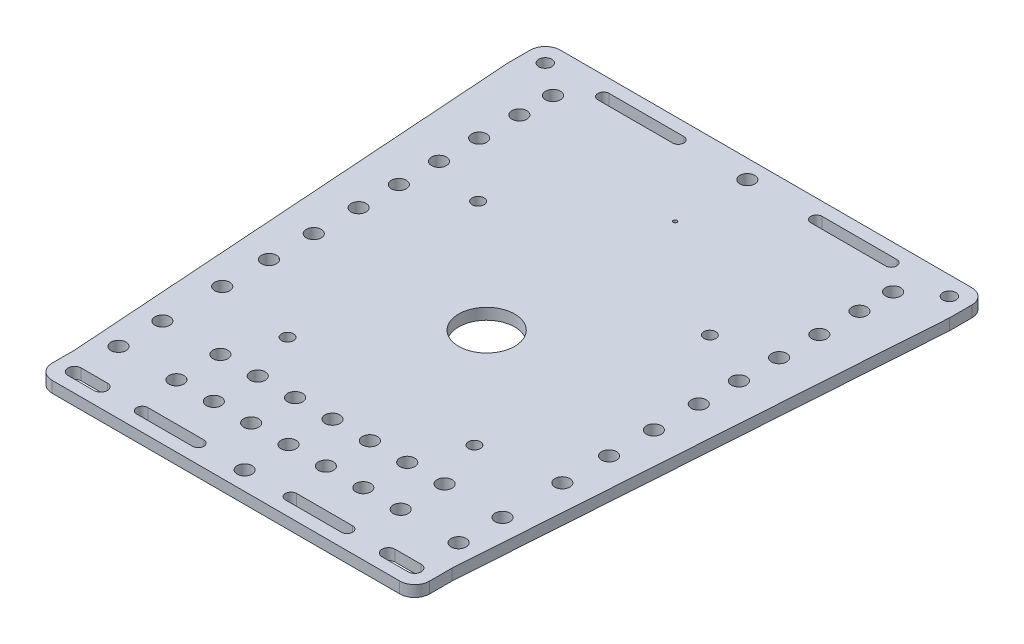
SolidWorks part; units mm, degrees
ref_plane "Front Plane" through (0, 0, 0) normal (0, 0, 1) x (1, 0, 0)
ref_plane "Top Plane" through (0, 0, 0) normal (0, 1, 0) x (1, 0, 0)
ref_plane "Right Plane" through (0, 0, 0) normal (1, 0, 0) x (0, 0, -1)
sketch "Sketch1" plane through (0, 0, 0) normal (0, 1, 0) x (1, 0, 0)
  line L0 (-12.0664, 0) -> (96.0664, 0)
  line L1 (42, 0) -> (42, -134.5)
  line L2 (-3.5, -134.5) -> (87.5, -134.5)
  line L3 (-17.0664, -5) -> (-8.5, -129.5)
  line L8 (-17.0664, 0) -> (-17.0664, 5)
  line L9 (-17.0664, 5) -> (96.0664, 5)
  line L10 (96.0664, 5) -> (101.0664, 5)
  line L11 (101.0664, 5) -> (101.0664, -5)
  line L13 (-17.0664, -5) -> (-17.0664, 0)
  line L14 (101.0664, -5) -> (92.5, -129.5)
  line L15 (-8.5, -134.5) -> (-8.5, -129.5)
  line L18 (92.5, -129.5) -> (92.5, -139.5)
  line L19 (92.5, -139.5) -> (-8.5, -139.5)
  line L20 (-8.5, -139.5) -> (-8.5, -134.5)
  line L21 (-3.5, -132.75) -> (3.5, -132.75)
  line L22 (-3.5, -136.25) -> (3.5, -136.25)
  line L23 (87.5, -132.75) -> (80.5, -132.75)
  line L24 (80.5, -136.25) -> (87.5, -136.25)
  circle A0 centre (-12.0664, 0) radius 1.75
  circle A1 centre (96.0664, 0) radius 1.75
  arc A2 (-3.5, -132.75) -> (-3.5, -136.25) centre (-3.5, -134.5) ccw
  arc A3 (87.5, -136.25) -> (87.5, -132.75) centre (87.5, -134.5) ccw
  arc A4 (3.5, -136.25) -> (3.5, -132.75) centre (3.5, -134.5) ccw
  arc A5 (80.5, -132.75) -> (80.5, -136.25) centre (80.5, -134.5) ccw
extrude "Boss-Extrude2" add sketch "Sketch1" along normal blind 3
sketch "Sketch2" plane through (0, 3, 0) normal (0, 1, 0) x (1, 0, 0)
  line L4 (11, -41.0284) -> (73, -41.0284)
  line L5 (73, -41.0284) -> (67, -98.0284)
  line L6 (67, -98.0284) -> (17, -98.0284)
  line L7 (17, -98.0284) -> (11, -41.0284)
  circle A0 centre (11, -41.0284) radius 1.6
  circle A1 centre (73, -41.0284) radius 1.6
  circle A2 centre (17, -98.0284) radius 1.6
  circle A3 centre (67, -98.0284) radius 1.6
extrude "Cut-Extrude1" cut sketch "Sketch2" against normal blind 3 contours A0 | A3 | A1 | A2
fillet "Fillet1" radius 4 4 edges at (-8.5, 1.5, 139.5) (92.5, 1.5, 139.5) (101.0664, 1.5, -5) (-17.0664, 1.5, -5)
sketch "Sketch3" plane through (0, 3, 0) normal (0, 1, 0) x (1, 0, 0)
  line L3 (54.3976, -134.5) -> (69.3976, -134.5) construction
  line L4 (29.6024, -134.5) -> (14.6024, -134.5) construction
  line L5 (23.5197, 0) -> (3.5197, 0) construction
  line L6 (23.5197, -1.5) -> (3.5197, -1.5)
  line L7 (23.5197, 1.5) -> (3.5197, 1.5)
  line L8 (29.6024, -136) -> (14.6024, -136)
  line L9 (29.6024, -133) -> (14.6024, -133)
  line L10 (54.3976, -136) -> (69.3976, -136)
  line L11 (54.3976, -133) -> (69.3976, -133)
  line L12 (60.4803, 0) -> (80.4803, 0) construction
  line L13 (60.4803, -1.5) -> (80.4803, -1.5)
  line L14 (60.4803, 1.5) -> (80.4803, 1.5)
  circle A0 centre (42, 0) radius 2
  circle A1 centre (-3.5, -95) radius 2
  circle A2 centre (-3.5, -111) radius 2
  circle A3 centre (42, -134.5) radius 2
  arc A4 (23.5197, -1.5) -> (23.5197, 1.5) centre (23.5197, 0) ccw
  arc A5 (3.5197, 1.5) -> (3.5197, -1.5) centre (3.5197, 0) ccw
  arc A6 (29.6024, -136) -> (29.6024, -133) centre (29.6024, -134.5) ccw
  arc A7 (14.6024, -133) -> (14.6024, -136) centre (14.6024, -134.5) ccw
  circle A8 centre (-3.5, -122.75) radius 2
  circle A10 centre (12, -111) radius 2
  circle A11 centre (22, -111) radius 2
  circle A12 centre (32, -111) radius 2
  circle A13 centre (42, -111) radius 2
  arc A14 (54.3976, -136) -> (54.3976, -133) centre (54.3976, -134.5) cw
  arc A15 (69.3976, -133) -> (69.3976, -136) centre (69.3976, -134.5) cw
  arc A16 (60.4803, -1.5) -> (60.4803, 1.5) centre (60.4803, 0) cw
  arc A17 (80.4803, 1.5) -> (80.4803, -1.5) centre (80.4803, 0) cw
  circle A18 centre (52, -111) radius 2
  circle A19 centre (62, -111) radius 2
  circle A20 centre (72, -111) radius 2
  circle A21 centre (87.5, -122.75) radius 2
  circle A22 centre (87.5, -111) radius 2
  circle A23 centre (87.5, -95) radius 2
  point P9 (13.5197, 0)
  point P14 (22.1024, -134.5)
  point P27 (61.8976, -134.5)
  point P48 (70.4803, 0)
extrude "Cut-Extrude2" cut sketch "Sketch3" against normal blind 3
sketch "Sketch4" plane through (0, 3, 0) normal (0, 1, 0) x (1, 0, 0)
  circle A0 centre (12, -122.75) radius 2
  circle A1 centre (22, -122.75) radius 2
  circle A2 centre (32, -122.75) radius 2
  circle A3 centre (42, -122.75) radius 2
  circle A4 centre (52, -122.75) radius 2
  circle A5 centre (62, -122.75) radius 2
  circle A6 centre (72, -122.75) radius 2
extrude "Cut-Extrude3" cut sketch "Sketch4" against normal blind 3
sketch "Sketch7" plane through (0, 3, 0) normal (0, 1, 0) x (1, 0, 0)
  circle A0 centre (42, -69.75) radius 7.5
extrude "Cut-Extrude5" cut sketch "Sketch7" against normal blind 3 contours A0
sketch "Sketch8" plane through (0, 3, 0) normal (0, 1, 0) x (1, 0, 0)
  line L6 (91.3284, -138.3284) -> (-7.3284, -138.3284)
  circle A1 centre (-3.5, -82.5) radius 2
  circle A2 centre (-3.5, -70.5) radius 2
  circle A3 centre (-3.5, -58.5) radius 2
  circle A4 centre (-3.5, -47.75) radius 2
  circle A5 centre (-3.5, -37) radius 2
  circle A6 centre (-3.5, -26.25) radius 2
  circle A7 centre (-3.5, -15.5) radius 2
  circle A8 centre (-3.5, -6.5) radius 2
  circle A13 centre (87.5, -6.5) radius 2
  arc A14 (88.5, -139.5) -> (92.5, -135.5) centre (88.5, -135.5) ccw construction
  arc A15 (-8.5, -135.5) -> (-4.5, -139.5) centre (-4.5, -135.5) ccw construction
  circle A16 centre (87.5, -15.5) radius 2
  circle A17 centre (87.5, -26.25) radius 2
  circle A18 centre (87.5, -37) radius 2
  circle A19 centre (87.5, -47.75) radius 2
  circle A20 centre (87.5, -58.5) radius 2
  circle A21 centre (87.5, -70.5) radius 2
  circle A22 centre (87.5, -82.5) radius 2
extrude "Cut-Extrude7" cut sketch "Sketch8" against normal blind 3 contours A6 | A5 | A2 | A1 | A8 | A7 | A4 | A3 | A13 | A16 | A17 | A18 | A19 | A20 | A21 | A22
sketch "Sketch9" plane through (0, 3, 0) normal (0, 1, 0) x (1, 0, 0)
  circle A1 centre (42, -19.3106) radius 0.5
extrude "Cut-Extrude8" cut sketch "Sketch9" against normal blind 3 contours A1
